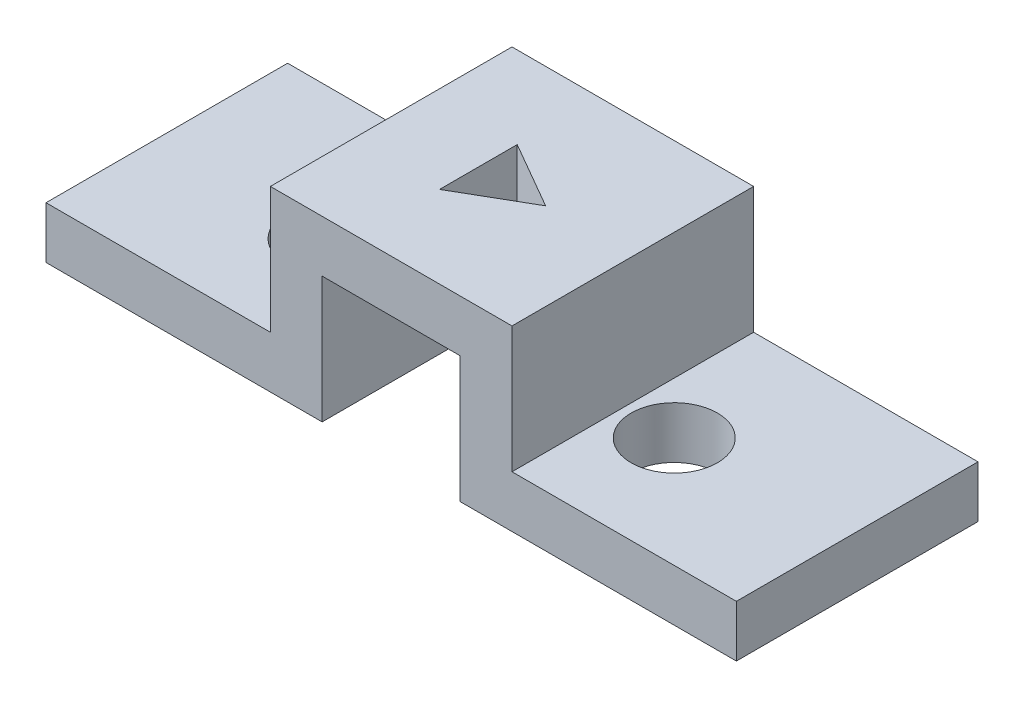
SolidWorks part; units mm, degrees
ref_plane "Front Plane" through (0, 0, 0) normal (0, 0, 1) x (1, 0, 0)
ref_plane "Top Plane" through (0, 0, 0) normal (0, 1, 0) x (1, 0, 0)
ref_plane "Right Plane" through (0, 0, 0) normal (1, 0, 0) x (0, 0, -1)
sketch "Sketch1" plane through (0, 0, 0) normal (0, 0, 1) x (1, 0, 0)
  line L0 (-10, -3.6591) -> (-2, -3.6591)
  line L1 (-2, -3.6591) -> (-2, 0)
  line L2 (-2, 0) -> (2, 0)
  line L3 (0, 0) -> (0, 1.5) construction
  line L4 (3.5, 1.5) -> (-3.5, 1.5)
  line L5 (-3.5, 1.5) -> (-3.5, -2.1591)
  line L6 (-3.5, -2.1591) -> (-10, -2.1591)
  line L7 (-10, -2.1591) -> (-10, -3.6591)
  line L8 (10, -2.1591) -> (10, -3.6591)
  line L9 (3.5, -2.1591) -> (10, -2.1591)
  line L10 (3.5, 1.5) -> (3.5, -2.1591)
  line L11 (2, -3.6591) -> (2, 0)
  line L12 (10, -3.6591) -> (2, -3.6591)
  dimension "D1" = 1.5
  dimension "D2" = 1.5
  dimension "D4" = 4
  dimension "D3" = 20
extrude "Boss-Extrude1" add sketch "Sketch1" along normal blind 7
sketch "Sketch2" plane through (0, -3.6591, 0) normal (0, -1, 0) x (1, 0, 0)
  circle A0 centre (5.0008, 3.8) radius 1.25
  dimension "D1" = 2.5
extrude "Cut-Extrude1" cut sketch "Sketch2" against normal up to next
ref_plane "Plane1" through (0, 0, 0) normal (-1, 0, 0) x (0, 0, 1)
mirror "Mirror1" about plane through (0, 0, 0) normal (-1, 0, 0) of "Cut-Extrude1"
sketch "Sketch3" plane through (0, 0, 0) normal (0, -1, 0) x (1, 0, 0)
  line L0 (0.9743, 3.5) -> (-0.9743, 4.625)
  line L1 (-0.9743, 4.625) -> (-0.9743, 2.375)
  line L2 (-0.9743, 2.375) -> (0.9743, 3.5)
  line L3 (-2, 7) -> (-2, 0) construction
  line L4 (0.9743, 3.5) -> (-0.9743, 3.5) construction
  point P2 (0, 3.5)
  point P4 (-2, 3.5)
  point P7 (-0.9743, 3.5)
  dimension "D1" = 2.25
extrude "Cut-Extrude2" cut sketch "Sketch3" against normal up to next
equation "\"D2@Sketch1\"=\"D1@Sketch1\""
